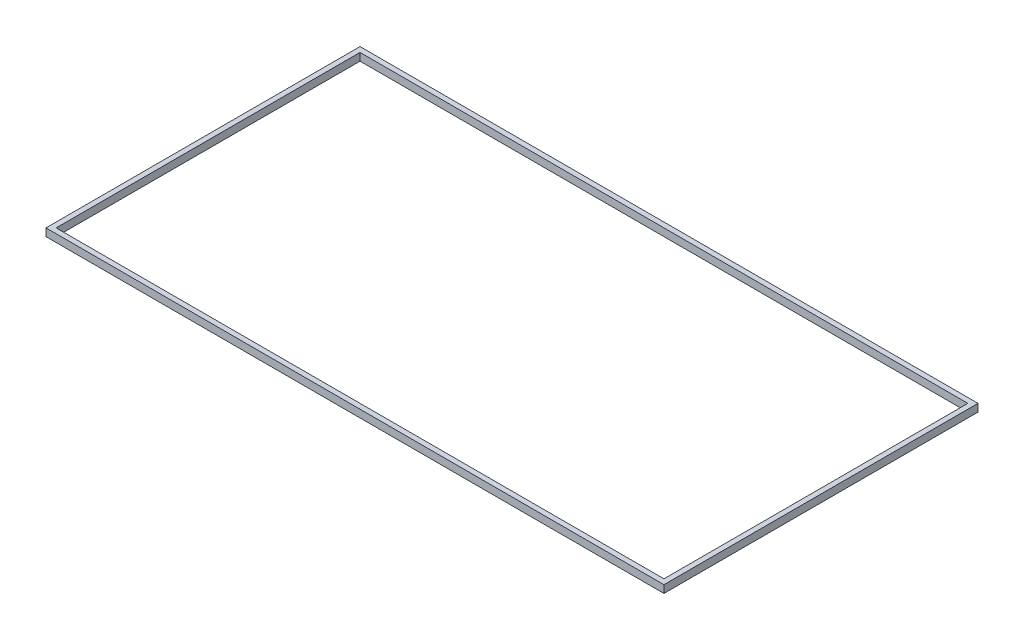
SolidWorks part; units mm, degrees
material "1060 Alloy"
ref_plane "Front Plane" through (0, 0, 0) normal (0, 0, 1) x (1, 0, 0)
ref_plane "Top Plane" through (0, 0, 0) normal (0, 1, 0) x (1, 0, 0)
ref_plane "Right Plane" through (0, 0, 0) normal (1, 0, 0) x (0, 0, -1)
sketch "Sketch1" plane through (0, 0, 0) normal (0, 1, 0) x (1, 0, 0)
  line L1 (-1200, -600) -> (1200, -600)
  line L2 (-1200, -600) -> (-1200, 600)
  line L3 (-1200, 600) -> (1200, 600)
  line L4 (1200, -600) -> (1200, 600)
  line L5 (-1200, -600) -> (1200, 600) construction
  line L6 (-1200, 600) -> (1200, -600) construction
  line L7 (-1220, -620) -> (1220, -620)
  line L8 (-1220, -620) -> (-1220, 620)
  line L9 (-1220, 620) -> (1220, 620)
  line L10 (1220, -620) -> (1220, 620)
  line L11 (-1220, -620) -> (1220, 620) construction
  line L12 (-1220, 620) -> (1220, -620) construction
  point P0 (0, 0)
  point P5 (0, 0)
  dimension "D1" = 20
  dimension "D2" = 20
  dimension "D3" = 2400
  dimension "D4" = 1200
extrude "Boss-Extrude1" add sketch "Sketch1" along normal mid plane 30
